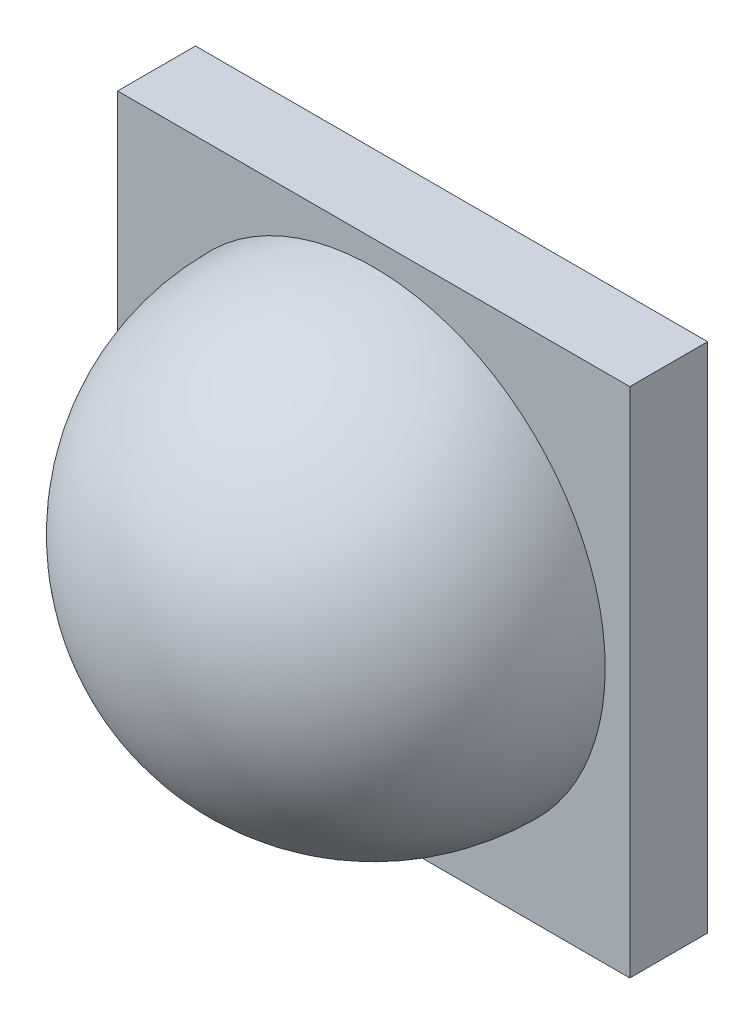
SolidWorks part; units mm, degrees
ref_plane "Front Plane" through (0, 0, 0) normal (0, 0, 1) x (1, 0, 0)
ref_plane "Top Plane" through (0, 0, 0) normal (0, 1, 0) x (1, 0, 0)
ref_plane "Right Plane" through (0, 0, 0) normal (1, 0, 0) x (0, 0, -1)
sketch "Sketch1" plane through (0, 0, 0) normal (0, 0, 1) x (1, 0, 0)
  line L1 (-2.5, 2.5) -> (2.5, 2.5)
  line L2 (-2.5, 2.5) -> (-2.5, -2.5)
  line L3 (-2.5, -2.5) -> (2.5, -2.5)
  line L4 (2.5, 2.5) -> (2.5, -2.5)
  line L5 (-2.5, 2.5) -> (2.5, -2.5) construction
  line L6 (-2.5, -2.5) -> (2.5, 2.5) construction
  point P0 (0, 0)
  dimension "D1" = 5
extrude "Boss-Extrude1" add sketch "Sketch1" along normal blind 0.76
sketch "Sketch2" plane through (0, 0, 0) normal (0, 1, 0) x (1, 0, 0)
  line L0 (0, -0.76) -> (2.26, -0.76)
  line L1 (2.5, -0.76) -> (-2.5, -0.76) construction
  line L2 (0, -0.76) -> (0, -3.02)
  line L3 (2.5, 0) -> (-2.5, 0) construction
  arc A0 (0, -3.02) -> (2.26, -0.76) centre (0, -0.76) ccw
  point P9 (0, 0)
  dimension "D1" = 3.02
revolve "Revolve1" add sketch "Sketch2" angle 360 about L2
